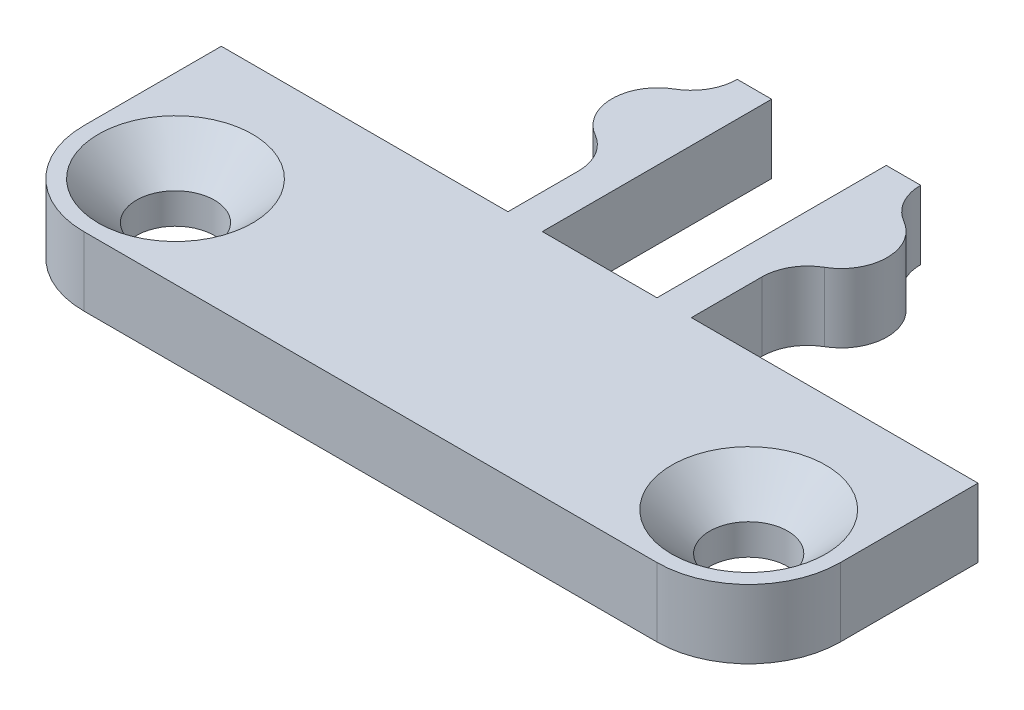
SolidWorks part; units mm, degrees
ref_plane "Front" through (0, 0, 0) normal (0, 0, 1) x (1, 0, 0)
ref_plane "Top" through (0, 0, 0) normal (0, 1, 0) x (1, 0, 0)
ref_plane "Right" through (0, 0, 0) normal (1, 0, 0) x (0, 0, -1)
sketch "Sketch1" plane through (0, 0, 0) normal (0, 1, 0) x (1, 0, 0)
  line L0 (-2.5, 0) -> (-2.5, 10)
  line L1 (-16.5, 0) -> (16.5, 0)
  line L2 (-16.5, 0) -> (-16.5, -10)
  line L3 (-16.5, -10) -> (16.5, -10)
  line L4 (16.5, 0) -> (16.5, -10)
  line L5 (4, 10) -> (2.5, 10)
  line L6 (-4, 3.0718) -> (-4, 0)
  line L7 (0, 0) -> (0, 11.0039) construction
  line L8 (4, 3.0718) -> (4, 0)
  line L9 (-2.5, 10) -> (-4, 10)
  line L10 (2.5, 0) -> (2.5, 10)
  arc A1 (-5, 8.2679) -> (-5, 4.8038) centre (-4, 6.5359) ccw
  arc A2 (5, 8.2679) -> (5, 4.8038) centre (4, 6.5359) cw
  arc A3 (5, 8.2679) -> (4, 10) centre (6, 10) cw
  arc A4 (-4, 10) -> (-5, 8.2679) centre (-6, 10) cw
  arc A5 (-5, 4.8038) -> (-4, 3.0718) centre (-6, 3.0718) cw
  arc A6 (5, 4.8038) -> (4, 3.0718) centre (6, 3.0718) ccw
  point P23 (4, 10)
  point P26 (-4, 4.5359)
  point P29 (4, 4.5359)
  point P30 (-4.3964, 10)
  point P31 (0, 0)
  dimension "D1" = 2
  dimension "D4" = 10
  dimension "D7" = 2
  dimension "D2" = 33
  dimension "D3" = 10
  dimension "D5" = 1.5
  dimension "D6" = 5
extrude "Boss-Extrude1" add sketch "Sketch1" along normal blind 3
sketch "Sketch2" plane through (0, 0, 0) normal (0, 1, 0) x (1, 0, 0)
  line L0 (12.5, -6) -> (-12.5, -6) construction
  line L1 (0, 0) -> (0, -6) construction
  line L3 (-16.5, -10) -> (16.5, -10) construction
  dimension "D1" = 25
  dimension "D2" = 4
hole_wizard "CSK for M3 SFHCS1" positions "Sketch3" profile "Sketch4" countersink size "M3" standard "ANSI Metric"
sketch "Sketch3" plane through (0, 3, 0) normal (0, 1, 0) x (1, 0, 0)
  point P0 (-12.5, -6)
  point P3 (12.5, -6)
sketch "Sketch4" plane through (-12.5, 3, 6) normal (1, 0, 0) x (0, 0, 1)
  line L0 (0, 0) -> (0, 11.0215)
  line L1 (0, 11.0215) -> (1.7, 10)
  line L2 (1.7, 10) -> (1.7, 1.66)
  line L3 (1.7, 1.66) -> (3.36, 0)
  line L5 (3.36, 0) -> (0, 0)
  line L6 (-1.7, 1.66) -> (-3.36, 0) construction
  line L10 (0, 11.0215) -> (-1.7, 10) construction
  line L11 (0, -6.35) -> (0, 107.95) construction
  dimension "Hole Dia." = 3.4
  dimension "Hole Depth" = 10
  dimension "Near C'Sink Dia." = 6.72
  dimension "Near C'Sink Angle" = 90
  dimension "Drill Angle" = 118
fillet "Fillet1" radius 4 2 edges at (-16.5, 1.5, 10) (16.5, 1.5, 10)
